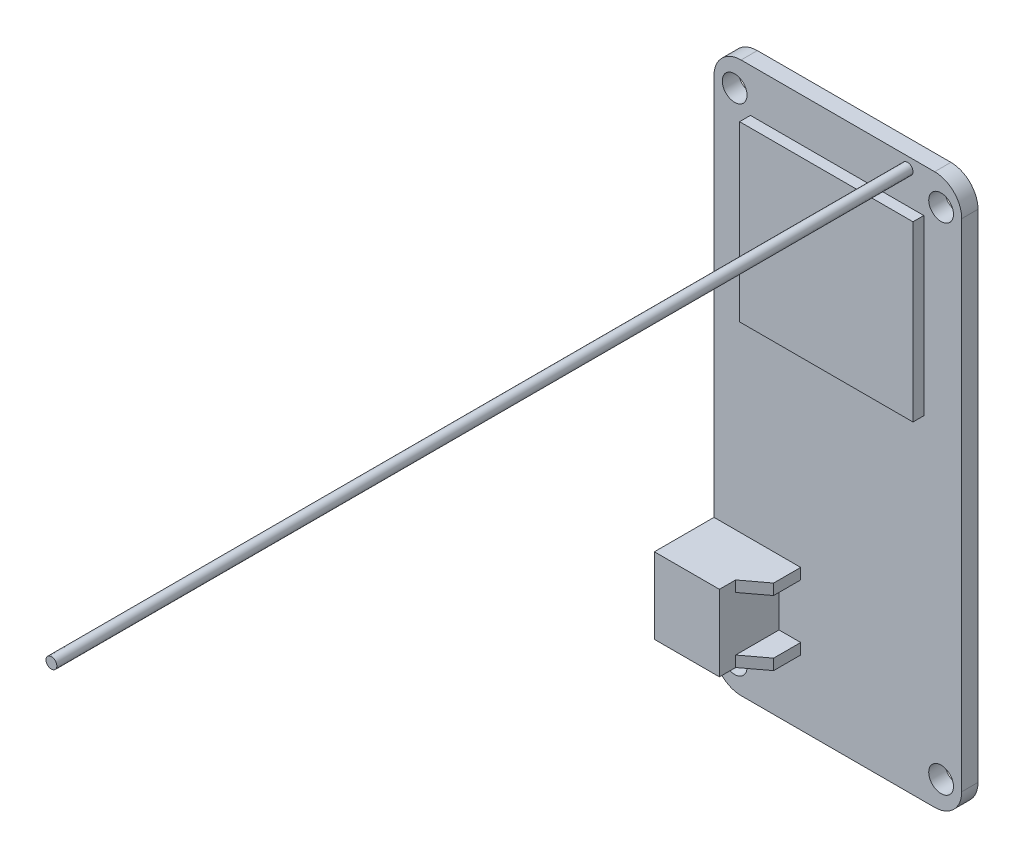
SolidWorks part; units mm, degrees
ref_plane "Front Plane" through (0, 0, 0) normal (0, 0, 1) x (1, 0, 0)
ref_plane "Top Plane" through (0, 0, 0) normal (0, 1, 0) x (1, 0, 0)
ref_plane "Right Plane" through (0, 0, 0) normal (1, 0, 0) x (0, 0, -1)
ref_plane "Plane1" through (0, 0, 3.5278) normal (0, 0, 1) x (1, 0, 0)
sketch "Sketch1" plane through (0, 0, 3.5278) normal (0, 0, 1) x (1, 0, 0)
  line L0 (-11.43, 22.9) -> (-11.43, -22.9)
  line L1 (-8.93, -25.4) -> (8.93, -25.4)
  line L2 (11.43, -22.9) -> (11.43, 22.9)
  line L3 (8.93, 25.4) -> (-8.93, 25.4)
  arc A0 (-11.43, -22.9) -> (-8.93, -25.4) centre (-8.93, -22.9) ccw
  arc A1 (8.93, -25.4) -> (11.43, -22.9) centre (8.93, -22.9) ccw
  arc A2 (11.43, 22.9) -> (8.93, 25.4) centre (8.93, 22.9) ccw
  arc A3 (-8.93, 25.4) -> (-11.43, 22.9) centre (-8.93, 22.9) ccw
  circle A4 centre (9.525, 22.86) radius 1.143
  circle A5 centre (-9.525, 22.86) radius 1.143
  circle A6 centre (-9.525, -22.86) radius 1.143
  circle A7 centre (9.525, -22.86) radius 1.143
extrude "Boss-Extrude1" add sketch "Sketch1" against normal blind 1.5
sketch "Croquis1" plane through (0, 0, 3.5278) normal (0, 0, 1) x (1, 0, 0)
  line L0 (11.43, -22.9) -> (11.43, 22.9) construction
  line L1 (-8.07, 21.4) -> (7.93, 21.4)
  line L2 (-8.07, 21.4) -> (-8.07, 5.4)
  line L3 (-8.07, 5.4) -> (7.93, 5.4)
  line L4 (7.93, 21.4) -> (7.93, 5.4)
  line L5 (-8.07, 21.4) -> (7.93, 5.4) construction
  line L6 (-8.07, 5.4) -> (7.93, 21.4) construction
  line L7 (8.93, 25.4) -> (-8.93, 25.4) construction
  point P0 (-0.07, 13.4)
  dimension "D1" = 16
  dimension "D2" = 16
  dimension "D3" = 3.5
  dimension "D4" = 4
extrude "Saliente-Extruir1" add sketch "Croquis1" along normal blind 1
sketch "Croquis2" plane through (0, 0, 3.5278) normal (0, 0, 1) x (1, 0, 0)
  line L0 (8.93, 25.4) -> (-8.93, 25.4) construction
  line L1 (11.43, -22.9) -> (11.43, 22.9) construction
  circle A0 centre (6.43, 24.4) radius 0.5
  dimension "D3" = 1
  dimension "D1" = 1
  dimension "D2" = 5
extrude "Saliente-Extruir2" add sketch "Croquis2" along normal blind 79
sketch "Croquis3" plane through (0, 0, 3.5278) normal (0, 0, 1) x (1, 0, 0)
  line L0 (-8.93, -25.4) -> (8.93, -25.4) construction
  line L1 (-11.43, -12.4) -> (-3.43, -12.4)
  line L2 (-11.43, -12.4) -> (-11.43, -19.4)
  line L3 (-11.43, -19.4) -> (-3.43, -19.4)
  line L4 (-3.43, -12.4) -> (-3.43, -13.4)
  line L5 (-11.43, -12.4) -> (-3.43, -19.4) construction
  line L6 (-11.43, -19.4) -> (-3.43, -12.4) construction
  line L7 (-11.43, 22.9) -> (-11.43, -22.9) construction
  line L8 (-3.43, -13.4) -> (-5.43, -13.4)
  line L9 (-5.43, -13.4) -> (-5.43, -18.4)
  line L10 (-5.43, -18.4) -> (-3.43, -18.4)
  line L11 (-3.43, -18.4) -> (-3.43, -19.4)
  point P0 (-7.43, -15.9)
  dimension "D1" = 6
  dimension "D2" = 7
  dimension "D3" = 8
  dimension "D4" = 1
  dimension "D5" = 1
  dimension "D6" = 2
extrude "Saliente-Extruir3" add sketch "Croquis3" along normal blind 5.5
sketch "Croquis4" plane through (0, -19.4, 0) normal (0, -1, 0) x (1, 0, 0)
  line L0 (-5.43, 9.0278) -> (-5.43, 7.5278)
  line L1 (-11.43, 9.0278) -> (-3.43, 9.0278) construction
  line L2 (-5.43, 7.5278) -> (-3.43, 6.0278)
  line L3 (-3.43, 9.0278) -> (-3.43, 3.5278) construction
  line L4 (-3.43, 6.0278) -> (-3.43, 9.0278)
  line L5 (-3.43, 9.0278) -> (-5.43, 9.0278)
  line L6 (-8.93, 3.5278) -> (8.93, 3.5278) construction
  dimension "D1" = 1.5
  dimension "D2" = 2.5
  dimension "D3" = 2
extrude "Cortar-Extruir1" cut sketch "Croquis4" against normal through all
